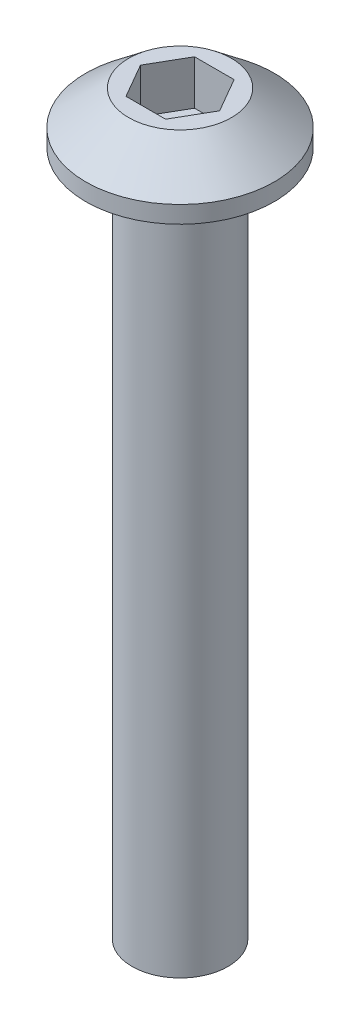
SolidWorks part; units mm, degrees
ref_plane "Front Plane" through (0, 0, 0) normal (0, 0, 1) x (1, 0, 0)
ref_plane "Top Plane" through (0, 0, 0) normal (0, 1, 0) x (1, 0, 0)
ref_plane "Right Plane" through (0, 0, 0) normal (1, 0, 0) x (0, 0, -1)
sketch "Sketch1" plane through (0, 0, 0) normal (0, 1, 0) x (1, 0, 0)
  circle A0 centre (0, 0) radius 1.4
  point P2 (0, 0)
  dimension "D1" = 2.8
extrude "Boss-Extrude1" add sketch "Sketch1" along normal blind 20
sketch "Sketch2" plane through (0, 20, 0) normal (0, 1, 0) x (1, 0, 0)
  circle A0 centre (0, 0) radius 2.75
  point P3 (0, 0)
  dimension "D1" = 5.5
extrude "Boss-Extrude2" add sketch "Sketch2" along normal blind 1.5
sketch "Sketch3" plane through (0, 0, 0) normal (1, 0, 0) x (0, 0, -1)
  line L0 (1.5, 21.5) -> (2.75, 20.5)
  line L1 (2.75, 21.5) -> (-2.75, 21.5) construction
  line L2 (2.75, 20) -> (2.75, 21.5) construction
  line L3 (2.75, 20.5) -> (2.75, 21.5)
  line L4 (2.75, 21.5) -> (1.5, 21.5)
  line L6 (0, 21.5) -> (0, 18.1194) construction
  point P6 (2.75, 20)
  point P8 (0, 21.5)
  dimension "D1" = 1.5
  dimension "D2" = 0.5
revolve "Cut-Revolve1" cut sketch "Sketch3" angle 360 about L6
sketch "Sketch4" plane through (0, 21.5, 0) normal (0, 1, 0) x (1, 0, 0)
  line L1 (1.1547, 0) -> (0.5774, 1)
  line L2 (0.5774, 1) -> (-0.5774, 1)
  line L3 (-0.5774, 1) -> (-1.1547, 0)
  line L4 (-1.1547, 0) -> (-0.5774, -1)
  line L5 (-0.5774, -1) -> (0.5774, -1)
  line L6 (0.5774, -1) -> (1.1547, 0)
  circle A0 centre (0, 0) radius 1 construction
  dimension "D1" = 2
extrude "Cut-Extrude1" cut sketch "Sketch4" against normal blind 1.3
